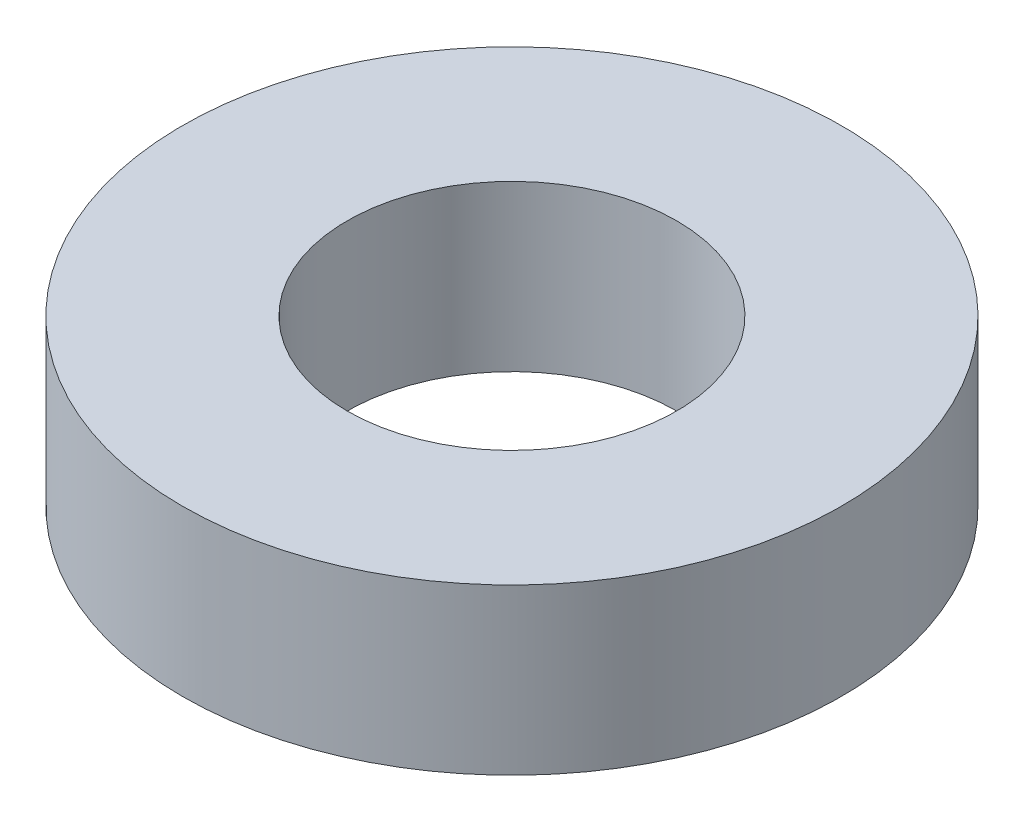
SolidWorks part; units mm, degrees
ref_plane "Front Plane" through (0, 0, 0) normal (0, 0, 1) x (1, 0, 0)
ref_plane "Top Plane" through (0, 0, 0) normal (0, 1, 0) x (1, 0, 0)
ref_plane "Right Plane" through (0, 0, 0) normal (1, 0, 0) x (0, 0, -1)
sketch "Sketch1" plane through (0, 0, 0) normal (0, 1, 0) x (1, 0, 0)
  circle A0 centre (0, 0) radius 3.175
  circle A1 centre (0, 0) radius 6.35
  dimension "D1" = 6.35
  dimension "D2" = 12.7
extrude "Boss-Extrude1" add sketch "Sketch1" along normal blind 3.175
